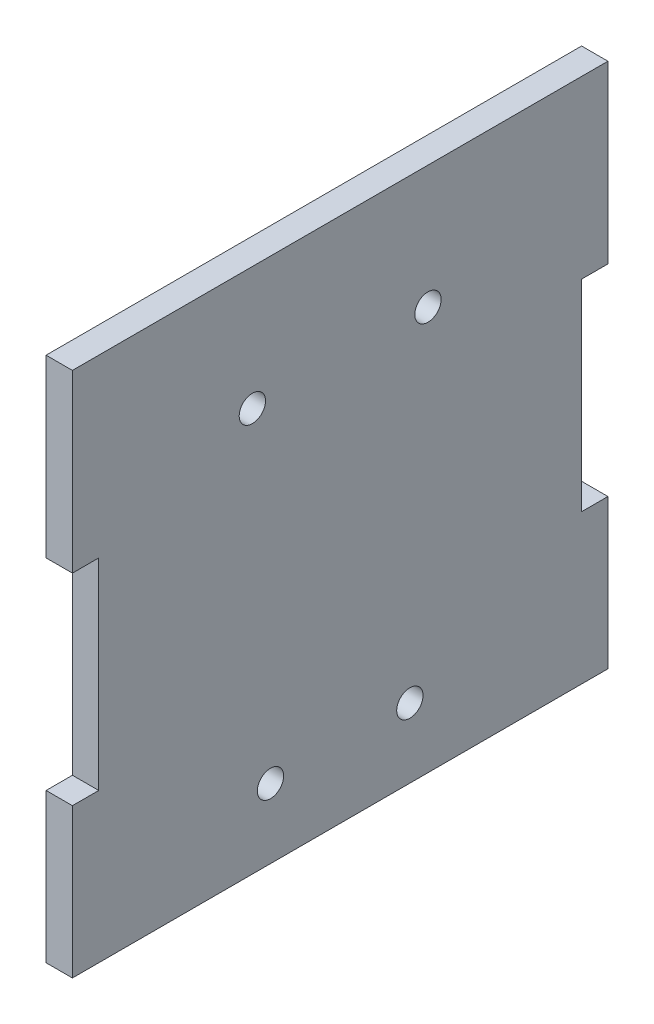
SolidWorks part; units mm, degrees
material "Acrilico TEC"
ref_plane "Front Plane" through (0, 0, 0) normal (0, 0, 1) x (1, 0, 0)
ref_plane "Top Plane" through (0, 0, 0) normal (0, 1, 0) x (1, 0, 0)
ref_plane "Right Plane" through (0, 0, 0) normal (1, 0, 0) x (0, 0, -1)
sketch "Sketch1" plane through (0, 0, 0) normal (1, 0, 0) x (0, 0, -1)
  line L0 (-27.5, 0) -> (27.5, 0)
  line L1 (-30.5, 39.94) -> (-30.5, 59.94)
  line L2 (27.5, 17) -> (30.5, 17)
  line L3 (-27.5, 17) -> (-27.5, 39.94)
  line L4 (30.5, 39.94) -> (27.5, 39.94)
  line L5 (-30.5, 0) -> (-30.5, 17)
  line L6 (27.5, 59.94) -> (-27.5, 59.94)
  line L7 (0, 59.94) -> (0, 0) construction
  line L8 (-30.5, 39.94) -> (-27.5, 39.94)
  line L9 (-27.5, 17) -> (-30.5, 17)
  line L10 (-30.5, 59.94) -> (-27.5, 59.94)
  line L11 (-30.5, 0) -> (-27.5, 0)
  line L13 (27.5, 0) -> (30.5, 0)
  line L14 (30.5, 0) -> (30.5, 17)
  line L15 (27.5, 17) -> (27.5, 39.94)
  line L16 (30.5, 39.94) -> (30.5, 59.94)
  line L17 (30.5, 59.94) -> (27.5, 59.94)
  dimension "D1" = 27.5
  dimension "D2" = 17
  dimension "D3" = 3
  dimension "D4" = 20
  dimension "D5" = 22.94
extrude "Boss-Extrude1" add sketch "Sketch1" along normal blind 3
sketch "Croquis1" plane through (0, 0, 0) normal (-1, 0, 0) x (0, 0, 1)
  line L0 (0, 0) -> (0, 59.94) construction
  line L1 (30.5, 0) -> (-30.5, 0) construction
  line L2 (-30.5, 59.94) -> (30.5, 59.94) construction
  circle A0 centre (-7.94, 7.91) radius 1.5
  circle A1 centre (7.94, 7.91) radius 1.5
  circle A2 centre (-10, 45.94) radius 1.5
  circle A3 centre (10, 45.94) radius 1.5
  dimension "D3" = 3
  dimension "D5" = 3
  dimension "D1" = 7.91
  dimension "D2" = 7.94
  dimension "D4" = 10
  dimension "D6" = 14
extrude "Cortar-Extruir1" cut sketch "Croquis1" against normal blind 10
